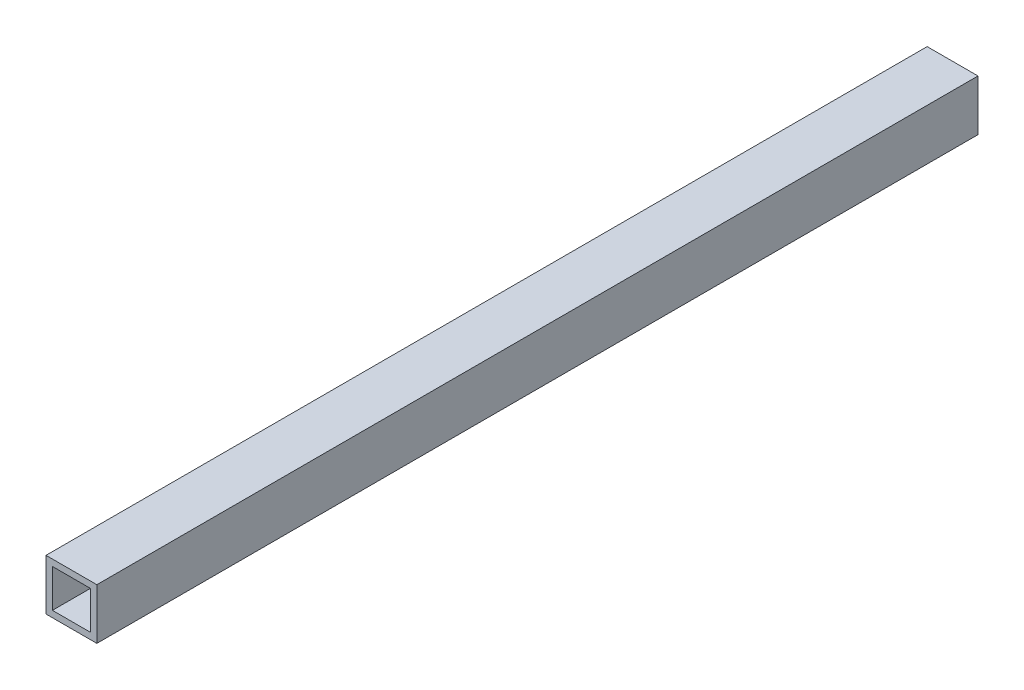
SolidWorks part; units mm, degrees
ref_plane "Front Plane" through (0, 0, 0) normal (0, 0, 1) x (1, 0, 0)
ref_plane "Top Plane" through (0, 0, 0) normal (0, 1, 0) x (1, 0, 0)
ref_plane "Right Plane" through (0, 0, 0) normal (1, 0, 0) x (0, 0, -1)
sketch "Sketch1" plane through (0, 0, 0) normal (0, 0, 1) x (1, 0, 0)
  line L1 (-6.06, 6.06) -> (6.06, 6.06)
  line L2 (-6.06, 6.06) -> (-6.06, -6.06)
  line L3 (-6.06, -6.06) -> (6.06, -6.06)
  line L4 (6.06, 6.06) -> (6.06, -6.06)
  line L5 (-6.06, 6.06) -> (6.06, -6.06) construction
  line L6 (-6.06, -6.06) -> (6.06, 6.06) construction
  line L7 (-4.53, 4.53) -> (4.53, 4.53)
  line L8 (-4.53, 4.53) -> (-4.53, -4.53)
  line L9 (-4.53, -4.53) -> (4.53, -4.53)
  line L10 (4.53, 4.53) -> (4.53, -4.53)
  line L11 (-4.53, 4.53) -> (4.53, -4.53) construction
  line L12 (-4.53, -4.53) -> (4.53, 4.53) construction
  point P0 (0, 0)
  point P6 (0, 0)
  dimension "D1" = 1.53
  dimension "D2" = 12.12
extrude "Boss-Extrude1" add sketch "Sketch1" along normal mid plane 210
equation "\"`300\"=220"
